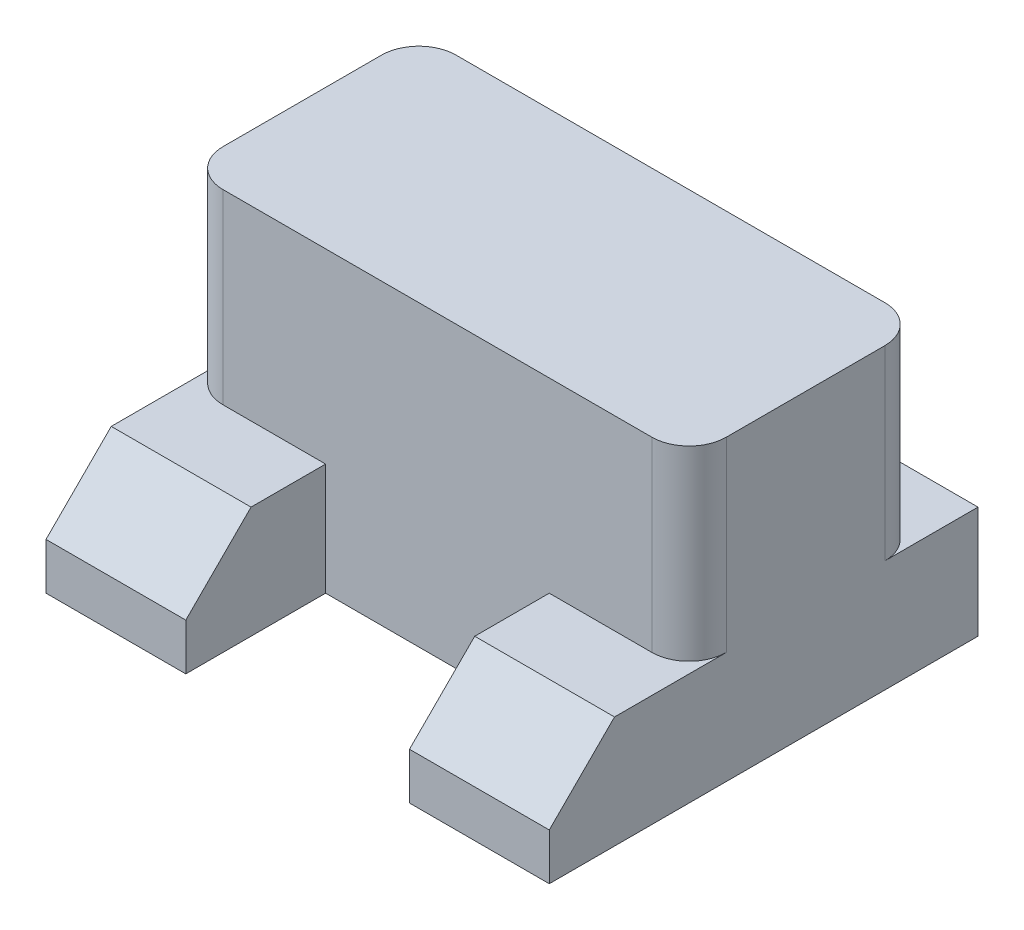
SolidWorks part; units mm, degrees
ref_plane "前视基准面" through (0, 0, 0) normal (0, 0, 1) x (1, 0, 0)
ref_plane "上视基准面" through (0, 0, 0) normal (0, 1, 0) x (1, 0, 0)
ref_plane "右视基准面" through (0, 0, 0) normal (1, 0, 0) x (0, 0, -1)
sketch "草图1" plane through (0, 0, 0) normal (0, 1, 0) x (1, 0, 0)
  line L0 (-2.7, 0.85) -> (-2.7, -0.85)
  line L1 (-2.3, 1.35) -> (2.3, 1.35)
  line L2 (-2.8, 0.85) -> (-2.8, -0.85)
  line L3 (-2.3, -1.35) -> (2.3, -1.35)
  line L4 (2.8, 0.85) -> (2.8, -0.85)
  line L5 (-2.8, 1.35) -> (2.8, -1.35) construction
  line L6 (-2.8, -1.35) -> (2.8, 1.35) construction
  line L7 (-2.3, -1.25) -> (2.3, -1.25)
  line L8 (2.7, 0.85) -> (2.7, -0.85)
  line L9 (-2.3, 1.25) -> (2.3, 1.25)
  arc A0 (2.3, 1.35) -> (2.8, 0.85) centre (2.3, 0.85) cw
  arc A1 (2.3, -1.35) -> (2.8, -0.85) centre (2.3, -0.85) ccw
  arc A2 (-2.8, -0.85) -> (-2.3, -1.35) centre (-2.3, -0.85) ccw
  arc A3 (-2.3, 1.35) -> (-2.8, 0.85) centre (-2.3, 0.85) ccw
  arc A4 (-2.3, 1.25) -> (-2.7, 0.85) centre (-2.3, 0.85) ccw
  arc A5 (-2.7, -0.85) -> (-2.3, -1.25) centre (-2.3, -0.85) ccw
  arc A6 (2.3, -1.25) -> (2.7, -0.85) centre (2.3, -0.85) ccw
  arc A7 (2.3, 1.25) -> (2.7, 0.85) centre (2.3, 0.85) cw
  point P0 (0, 0)
  dimension "D3" = 0.5
  dimension "D1" = 5.6
  dimension "D2" = 2.7
  dimension "D4" = 0.1
extrude "凸台-拉伸3" add sketch "草图1" along normal blind 2 and the other way blind 1.2 contours A4 L0 A5 L7 A6 L8 A7 L9
sketch "草图2" plane through (0, 0, 0) normal (0, 1, 0) x (1, 0, 0)
  line L1 (-2.7, 1.25) -> (2.7, 1.25)
  line L2 (-2.7, 1.25) -> (-2.7, -1.25)
  line L3 (-2.7, -1.25) -> (2.7, -1.25)
  line L4 (2.7, 1.25) -> (2.7, -1.25)
  line L5 (-2.7, 1.25) -> (2.7, -1.25) construction
  line L6 (-2.7, -1.25) -> (2.7, 1.25) construction
  point P0 (0, 0)
  dimension "D1" = 5.4
  dimension "D2" = 2.5
extrude "凸台-拉伸4" add sketch "草图2" against normal blind 1.2
ref_plane "基准面4" through (0, 0, -1.25) normal (0, 0, -1) x (-1, 0, 0)
ref_plane "基准面5" through (0, 0, 1.25) normal (0, 0, 1) x (1, 0, 0)
ref_plane "基准面6" through (0, -1.2, 0) normal (0, -1, 0) x (-1, 0, 0)
sketch "草图5" plane through (0, -1.2, 0) normal (0, -1, 0) x (-1, 0, 0)
  line L1 (2, 0.9) -> (-2, 0.9)
  line L2 (2, 0.9) -> (2, -0.6)
  line L3 (2, -0.6) -> (-2, -0.6)
  line L4 (-2, 0.9) -> (-2, -0.6)
  point P6 (0, -0.6)
  dimension "D1" = 4
  dimension "D2" = 1.5
extrude "凸台-拉伸7" add sketch "草图5" along normal blind 0.5
sketch "草图6" plane through (0, 0, -1.25) normal (0, 0, -1) x (-1, 0, 0)
  line L0 (-2, -1.2) -> (2, -1.2) construction
  line L1 (2.7, 0) -> (1.2, 0)
  line L2 (2.7, 0) -> (2.7, -1.2)
  line L3 (2.7, -1.2) -> (1.2, -1.2)
  line L4 (1.2, 0) -> (1.2, -1.2)
  line L5 (2.7, -1.2) -> (-2.7, -1.2) construction
  line L6 (-2.7, 0) -> (-1.2, 0)
  line L7 (-2.7, 0) -> (-2.7, -1.2)
  line L8 (-2.7, -1.2) -> (-1.2, -1.2)
  line L9 (-1.2, 0) -> (-1.2, -1.2)
  dimension "D1" = 2.4
extrude "凸台-拉伸8" add sketch "草图6" along normal blind 0.6
sketch "草图7" plane through (0, 0, 1.25) normal (0, 0, 1) x (1, 0, 0)
  line L4 (2.7, 0) -> (1.2, 0)
  line L5 (1.2, 0) -> (1.2, -1.2)
  line L6 (1.2, -1.2) -> (2.7, -1.2)
  line L7 (2.7, -1.2) -> (2.7, 0)
  line L8 (2.7, 0) -> (1.2, 0)
  line L9 (1.2, 0) -> (1.2, -1.2)
  line L10 (1.2, -1.2) -> (2.7, -1.2)
  line L11 (2.7, -1.2) -> (2.7, 0)
  line L12 (-1.2, 0) -> (-2.7, 0)
  line L13 (-1.2, -1.2) -> (-1.2, 0)
  line L14 (-2.7, -1.2) -> (-1.2, -1.2)
  line L15 (-2.7, 0) -> (-2.7, -1.2)
  line L16 (-1.2, 0) -> (-2.7, 0)
  line L17 (-1.2, -1.2) -> (-1.2, 0)
  line L18 (-2.7, -1.2) -> (-1.2, -1.2)
  line L19 (-2.7, 0) -> (-2.7, -1.2)
  dimension "D1" = 0
  dimension "D2" = 0
extrude "凸台-拉伸9" add sketch "草图7" along normal blind 1.5
chamfer "倒角2" distance 0.7 angle 45 2 edges at (-1.95, 0, 2.75) (1.95, 0, 2.75)
